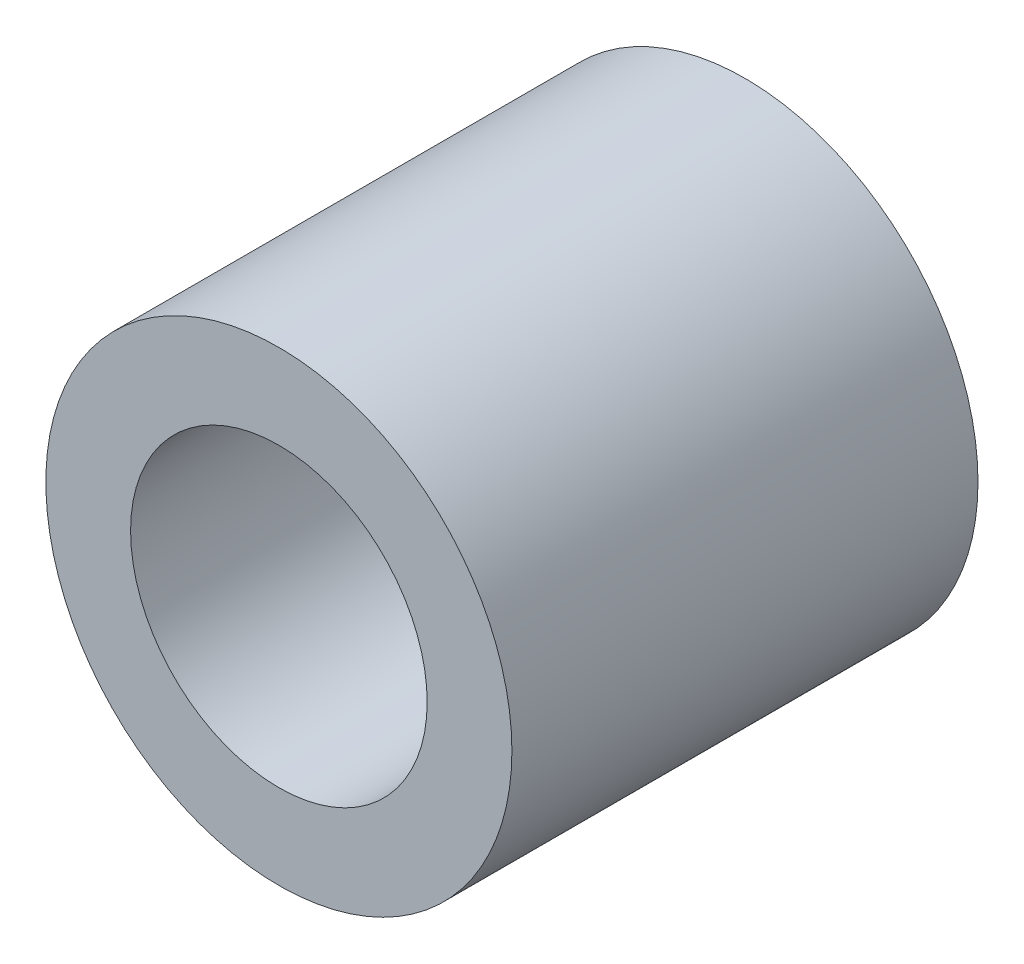
SolidWorks part; units mm, degrees
material "ABS"
ref_plane "前视基准面" through (0, 0, 0) normal (0, 0, 1) x (1, 0, 0)
ref_plane "上视基准面" through (0, 0, 0) normal (0, 1, 0) x (1, 0, 0)
ref_plane "右视基准面" through (0, 0, 0) normal (1, 0, 0) x (0, 0, -1)
sketch "草图1" plane through (0, 0, 0) normal (0, 0, 1) x (1, 0, 0)
  circle A0 centre (0, 0) radius 1.75
  circle A1 centre (0, 0) radius 2.75
  dimension "D1" = 3.5
  dimension "D2" = 5.5
extrude "凸台-拉伸1" add sketch "草图1" along normal blind 5.5
